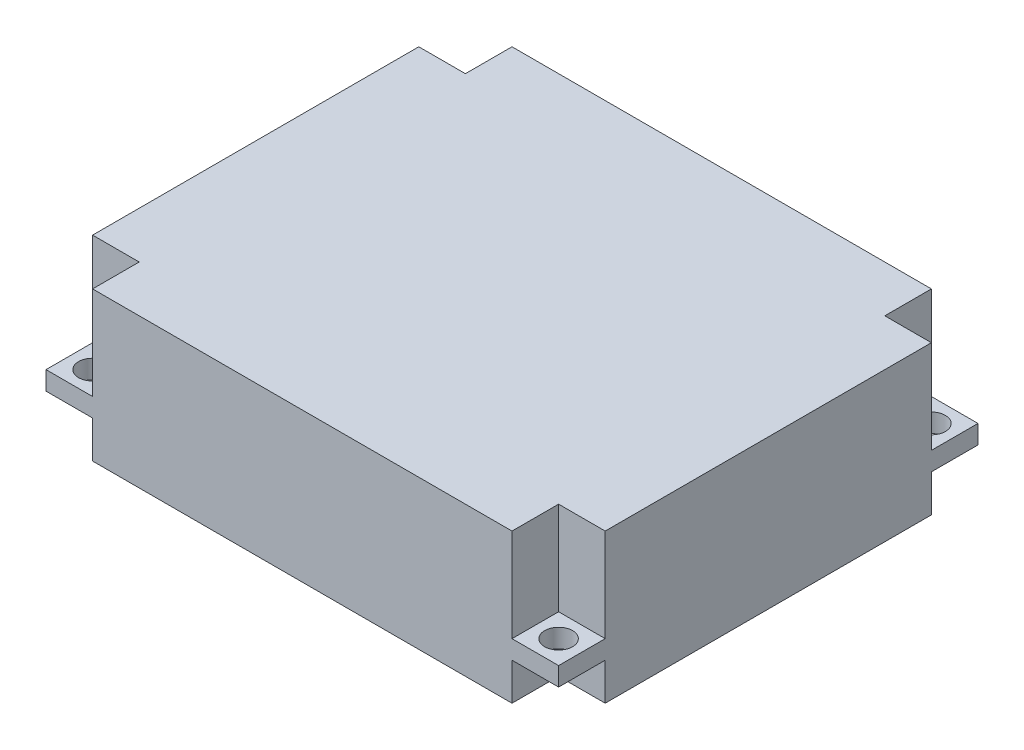
SolidWorks part; units mm, degrees
ref_plane "Спереди" through (0, 0, 0) normal (0, 0, 1) x (1, 0, 0)
ref_plane "Сверху" through (0, 0, 0) normal (0, 1, 0) x (1, 0, 0)
ref_plane "Справа" through (0, 0, 0) normal (1, 0, 0) x (0, 0, -1)
sketch "Эскиз1" plane through (0, 0, 0) normal (0, 1, 0) x (1, 0, 0)
  line L0 (-27.5, 0) -> (27.5, 0) construction
  line L1 (-27.5, 22.5) -> (27.5, 22.5)
  line L2 (-27.5, 22.5) -> (-27.5, -22.5)
  line L3 (-27.5, -22.5) -> (27.5, -22.5)
  line L4 (27.5, 22.5) -> (27.5, -22.5)
  line L6 (0, 22.5) -> (0, -22.5) construction
  point P6 (0, 0)
  dimension "D1" = 55
  dimension "D2" = 45
extrude "плата" add sketch "Эскиз1" along normal blind 2
sketch "Эскиз2" plane through (0, 2, 0) normal (0, 1, 0) x (1, 0, 0)
  line L0 (0, 22.5) -> (0, -22.5) construction
  line L1 (27.5, 22.5) -> (-27.5, 22.5) construction
  line L2 (-27.5, -22.5) -> (27.5, -22.5) construction
  line L3 (0, 20) -> (0, -20) construction
  line L4 (27.5, -22.5) -> (27.5, 22.5) construction
  line L5 (27.5, 0) -> (-27.5, 0) construction
  line L6 (-27.5, 22.5) -> (-27.5, -22.5) construction
  line L7 (-25, 20) -> (25, 20) construction
  line L8 (-25, 20) -> (-25, -20) construction
  line L9 (-25, -20) -> (25, -20) construction
  line L10 (25, 20) -> (25, -20) construction
  line L12 (-25, 0) -> (25, 0) construction
  circle A0 centre (-25, 20) radius 1.5
  circle A1 centre (25, 20) radius 1.5
  circle A2 centre (25, -20) radius 1.5
  circle A3 centre (-25, -20) radius 1.5
  point P24 (0, 0)
  dimension "D3" = 3
  dimension "D1" = 50
  dimension "D2" = 40
extrude "крепежные отверстия" cut sketch "Эскиз2" against normal through all and the other way through all
sketch "Эскиз3" plane through (0, 2, 0) normal (0, 1, 0) x (1, 0, 0)
  line L0 (-27.5, 17.5) -> (-22.5, 17.5)
  line L1 (-27.5, 22.5) -> (-27.5, -22.5) construction
  line L2 (-22.5, 17.5) -> (-22.5, 22.5)
  line L3 (27.5, 22.5) -> (-27.5, 22.5) construction
  line L4 (-22.5, 22.5) -> (22.5, 22.5)
  line L5 (22.5, 22.5) -> (22.5, 17.5)
  line L6 (22.5, 17.5) -> (27.5, 17.5)
  line L7 (27.5, -22.5) -> (27.5, 22.5) construction
  line L8 (27.5, 17.5) -> (27.5, -17.5)
  line L9 (27.5, -17.5) -> (22.5, -17.5)
  line L10 (22.5, -17.5) -> (22.5, -22.5)
  line L11 (-27.5, -22.5) -> (27.5, -22.5) construction
  line L12 (22.5, -22.5) -> (-22.5, -22.5)
  line L13 (-22.5, -22.5) -> (-22.5, -17.5)
  line L14 (-22.5, -17.5) -> (-27.5, -17.5)
  line L15 (-27.5, -17.5) -> (-27.5, 17.5)
  dimension "D1" = 5
  dimension "D2" = 5
extrude "выступы" add sketch "Эскиз3" along normal blind 10 and the other way blind 6
